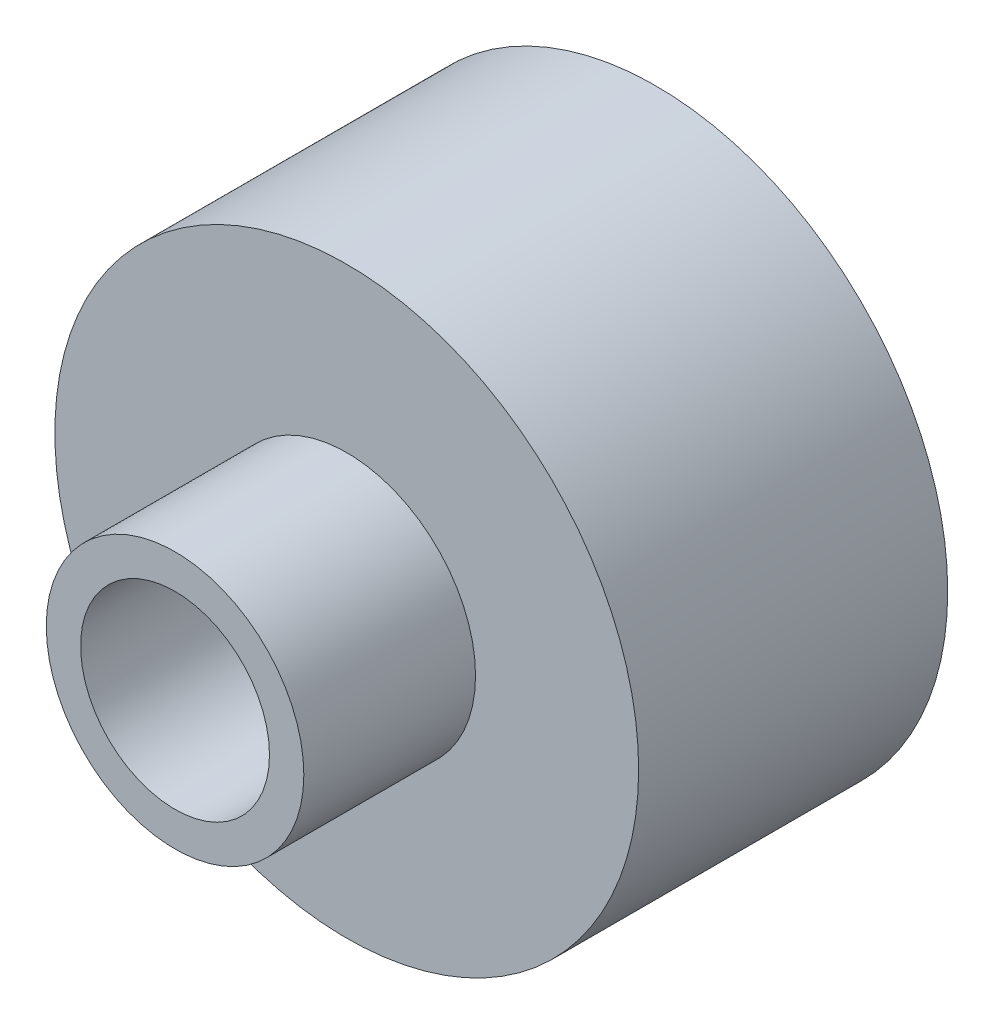
SolidWorks part; units mm, degrees
material "Настроенная пользователем пластмасса"
ref_plane "Спереди" through (0, 0, 0) normal (0, 0, 1) x (1, 0, 0)
ref_plane "Сверху" through (0, 0, 0) normal (0, 1, 0) x (1, 0, 0)
ref_plane "Справа" through (0, 0, 0) normal (1, 0, 0) x (0, 0, -1)
sketch "Эскиз1" plane through (0, 0, 0) normal (0, 1, 0) x (1, 0, 0)
  line L0 (2.75, -14) -> (3.75, -14)
  line L1 (3.75, -14) -> (3.75, -9)
  line L2 (3.75, -9) -> (8.5, -9)
  line L3 (8.5, -9) -> (8.5, 0)
  line L4 (8.5, 0) -> (2.75, 0)
  line L5 (2.75, 0) -> (2.75, -14)
  line L6 (0, 0) -> (0, -14) construction
revolve "Повернуть1" add sketch "Эскиз1" angle 360 about L6
